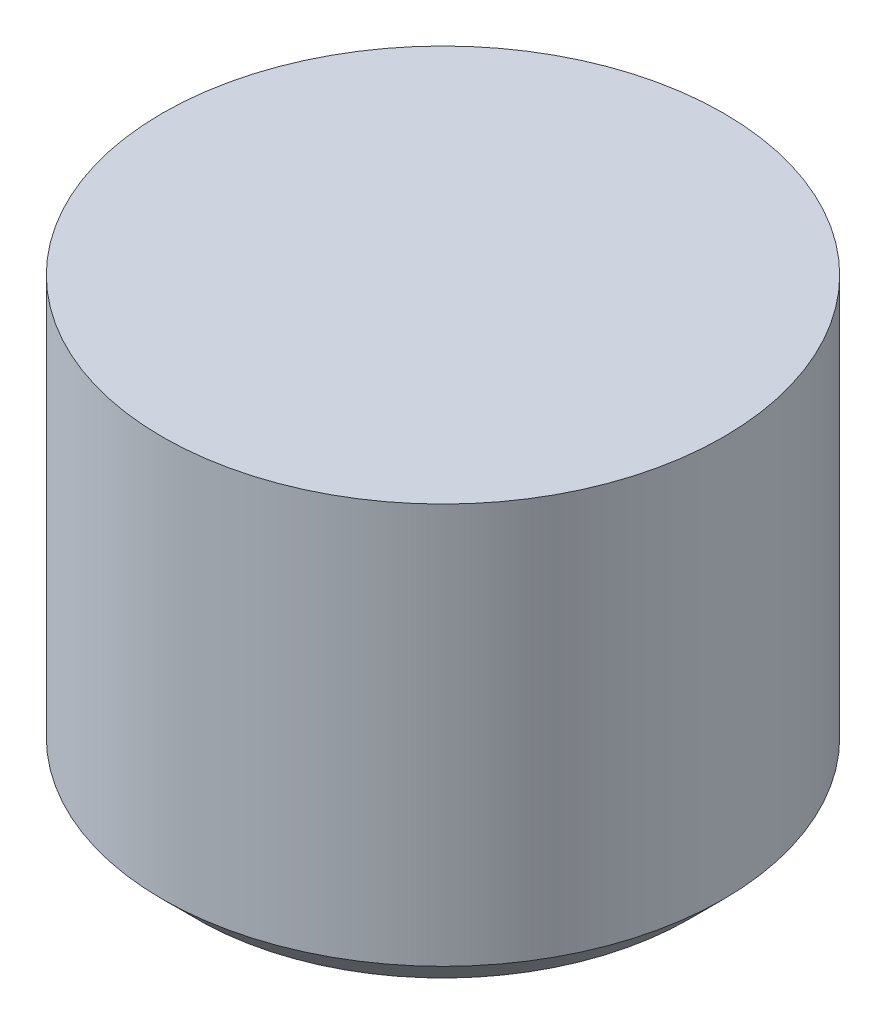
SolidWorks part; units mm, degrees
ref_plane "Płaszczyzna przednia" through (0, 0, 0) normal (0, 0, 1) x (1, 0, 0)
ref_plane "Płaszczyzna górna" through (0, 0, 0) normal (0, 1, 0) x (1, 0, 0)
ref_plane "Płaszczyzna prawa" through (0, 0, 0) normal (1, 0, 0) x (0, 0, -1)
sketch "Szkic1" plane through (0, 0, 0) normal (0, 0, 1) x (1, 0, 0)
  line L0 (0, 17.4168) -> (0, -20.4432) construction
  line L1 (0, 17.4168) -> (-24.425, 17.4168)
  line L2 (-24.425, 17.4168) -> (-24.425, -17.4432)
  line L3 (-21.425, -20.4432) -> (0, -20.4432)
  line L4 (0, 17.4168) -> (0, -20.4432)
  line L5 (-24.425, -17.4432) -> (-21.425, -20.4432)
  point P5 (-24.425, -20.4432)
  dimension "D1" = 24.425
  dimension "D2" = 37.86
  dimension "D3" = 21.425
revolve "Obrót1" add sketch "Szkic1" angle 360 about L0
